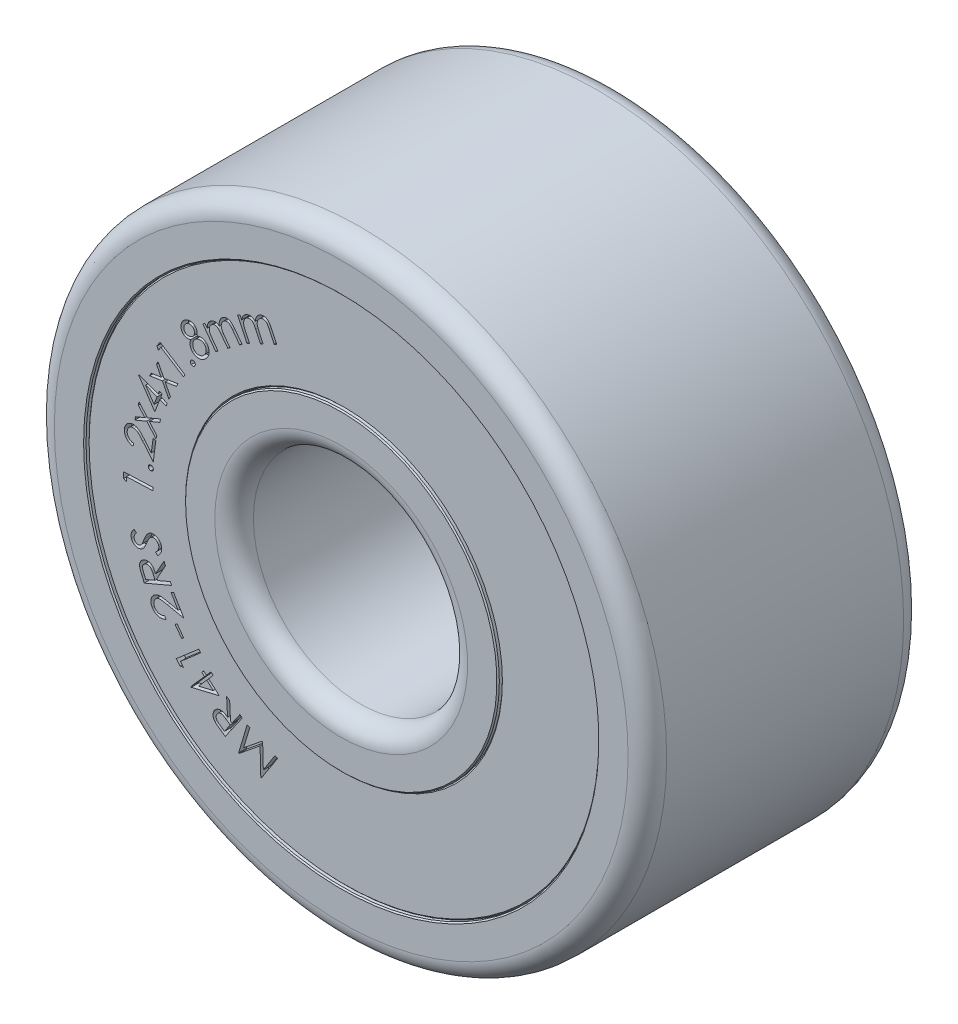
SolidWorks part; units mm, degrees
material "AISI 316 Annealed Stainless Steel Bar (SS)"
ref_plane "Front" through (0, 0, 0) normal (0, 0, 1) x (1, 0, 0)
ref_plane "Top" through (0, 0, 0) normal (0, 1, 0) x (1, 0, 0)
ref_plane "Right" through (0, 0, 0) normal (1, 0, 0) x (0, 0, -1)
sketch "LAYOUT R" plane through (0, 0, 0) normal (1, 0, 0) x (0, 0, -1)
  line L0 (-0.9, 0.7) -> (0.9, 0.7)
  line L1 (0.9, -2) -> (-0.9, -2) construction
  line L2 (0.9, -2) -> (0.9, 2) construction
  line L3 (0.9, 2) -> (-0.9, 2)
  line L4 (-0.9, -2) -> (-0.9, 2) construction
  line L5 (0.9, -2) -> (-0.9, 2) construction
  line L6 (0.9, 2) -> (-0.9, -2) construction
  line L7 (-0.9, 1.025) -> (0.9, 1.025)
  line L8 (-0.9, 1.675) -> (0.9, 1.675)
  line L11 (-17.5, 0) -> (17.5, 0) construction
  line L12 (-0.9, 2) -> (-0.9, 1.675)
  line L13 (0.9, 2) -> (0.9, 1.675)
  line L14 (-0.9, 1.675) -> (-0.9, 1.025)
  line L15 (0.9, 1.675) -> (0.9, 1.025)
  line L16 (-0.9, 1.025) -> (-0.9, 0.7)
  line L17 (0.9, 1.025) -> (0.9, 0.7)
  line L18 (-0.88, 1.675) -> (-0.88, 1.025)
  line L19 (0.88, 1.675) -> (0.88, 1.025)
  point P0 (0, 0)
  point P15 (0, 0)
  dimension "D1" = 1.8
  dimension "D2" = 4
  dimension "D3" = 0.7
  dimension "D6" = 0.02
  dimension "D7" = 0.02
  dimension "D4" = 1.025
  dimension "D5" = 1.675
sketch "Sketch R, INNER BODY" plane through (0, 0, 0) normal (1, 0, 0) x (0, 0, -1)
  line L0 (-0.9, 0.7) -> (0.9, 0.7) construction
  line L2 (-0.9, 1.025) -> (0.9, 1.025) construction
  line L4 (-0.9, 0.7) -> (0.9, 0.7)
  line L6 (-0.9, 1.025) -> (0.9, 1.025)
  line L8 (0.9, 1.025) -> (0.9, 0.7) construction
  line L9 (-0.9, 1.025) -> (-0.9, 0.7) construction
  line L10 (0.9, 1.025) -> (0.9, 0.7)
  line L11 (-0.9, 1.025) -> (-0.9, 0.7)
  line L12 (-17.5, 0) -> (17.5, 0) construction
  line L13 (-17.5, 0) -> (17.5, 0) construction
sketch "Sketch R, OUTER BODY" plane through (0, 0, 0) normal (1, 0, 0) x (0, 0, -1)
  line L2 (-0.9, 1.675) -> (0.9, 1.675) construction
  line L3 (0.9, 2) -> (-0.9, 2) construction
  line L6 (-0.9, 1.675) -> (0.9, 1.675)
  line L7 (0.9, 2) -> (-0.9, 2)
  line L8 (-17.5, 0) -> (17.5, 0) construction
  line L9 (-17.5, 0) -> (17.5, 0) construction
  line L10 (0.9, 2) -> (0.9, 1.675) construction
  line L11 (-0.9, 2) -> (-0.9, 1.675) construction
  line L12 (0.9, 2) -> (0.9, 1.675)
  line L13 (-0.9, 2) -> (-0.9, 1.675)
sketch "Sketch R, SEAL FACES" plane through (0, 0, 0) normal (1, 0, 0) x (0, 0, -1)
  line L0 (-17.5, 0) -> (17.5, 0) construction
  line L1 (-17.5, 0) -> (17.5, 0) construction
  line L3 (-0.9, 1.025) -> (0.9, 1.025) construction
  line L5 (-0.9, 1.675) -> (0.9, 1.675) construction
  line L7 (-0.88, 1.025) -> (0.88, 1.025)
  line L9 (-0.88, 1.675) -> (0.88, 1.675)
  line L10 (0.88, 1.675) -> (0.88, 1.025) construction
  line L11 (-0.88, 1.675) -> (-0.88, 1.025) construction
  line L12 (0.88, 1.675) -> (0.88, 1.025)
  line L13 (-0.88, 1.675) -> (-0.88, 1.025)
revolve "Revolve INNER BODY" add sketch "Sketch R, INNER BODY" angle 360 about L13
fillet "Fillet INNER BODY" radius 0.126 2 edges at (0.7, 0, 0.9) (0.7, 0, -0.9)
chamfer "Chamfer INNER BODY" distance 0.008 angle 45 2 edges at (1.025, 0, -0.9) (1.025, 0, 0.9)
revolve "Revolve OUTER BODY" add sketch "Sketch R, OUTER BODY" angle 360 about L9
fillet "Fillet OUTER BODY" radius 0.126 2 edges at (2, 0, -0.9) (2, 0, 0.9)
chamfer "Chamfer OUTER BODY" distance 0.008 angle 45 2 edges at (1.675, 0, 0.9) (1.675, 0, -0.9)
revolve "Revolve SEALS" add sketch "Sketch R, SEAL FACES" angle 360 about L1
chamfer "Chamfer SEALS" distance 0.008 angle 45 4 edges at (1.025, 0, -0.88) (1.675, 0, -0.88) (1.675, 0, 0.88) (1.025, 0, 0.88)
sketch "Sketch TEXT RADIUS 1 — MANUALLY ASSIGN TEXT AND FONT SIZE (FROM EQUATIONS)" plane through (0, 0, 0.88) normal (0, 0, 1) x (1, 0, 0)
  circle A0 centre (0, 0) radius 1.2525 construction
  text T0 "MR41-2RS  1.2x4x1.8mm" font "Century Gothic" height 0.195
  dimension "D1" = 2.505
extrude "Cut-Extrude SEAL LABEL 1" cut sketch "Sketch TEXT RADIUS 1 — MANUALLY ASSIGN TEXT AND FONT SIZE (FROM EQUATIONS)" against normal blind 0.05
sketch "Sketch TEXT RADIUS 2 — MANUALLY ASSIGN TEXT AND FONT SIZE (FROM EQUATIONS)" plane through (0, 0, -0.88) normal (0, 0, -1) x (-1, 0, 0)
  circle A0 centre (0, 0) radius 1.2525 construction
  text T0 "MR41-2RS  1.2x4x1.8mm" font "Century Gothic" height 0.195
  dimension "D1" = 2.505
extrude "Cut-Extrude SEAL LABEL 2" cut sketch "Sketch TEXT RADIUS 2 — MANUALLY ASSIGN TEXT AND FONT SIZE (FROM EQUATIONS)" against normal blind 0.05
equation "\"_i__BORE\"= 1.4"
equation "\"_i__OUTSIDE_DIAMETER\"= 4"
equation "\"_i__WIDTH\"= 1.8"
equation "\"_i_optional__TEXT_RADIUS_ADJUSTMENT\"= 0"
equation "\"_output__FONT_SIZE_mm\"= \"BODY_SPAN__SEAL__OF_RADIUS\" * \"param__FONT_SIZE_RATIO\"'MANUALLY ASSIGN TO FONT"
equation "\"BODY__HALF_WIDTH\"= \"_i__WIDTH\" / 2"
equation "\"BODY_SPAN___OF_DIAMETER\"= \"_i__OUTSIDE_DIAMETER\" - \"_i__BORE\""
equation "\"BODY_SPAN___OF_RADIUS\"= \"BODY_SPAN___OF_DIAMETER\" / 2"
equation "\"BODY_SPAN__BORE_AND_OD__OF RADIUS\"= ( \"BODY_SPAN___OF_RADIUS\" - \"BODY_SPAN__SEAL__OF_RADIUS\" ) / 2"
equation "\"BODY_SPAN__SEAL__OF_RADIUS\"= \"BODY_SPAN___OF_RADIUS\" * \"param__SEAL_PANEL_SPAN__RATIO_OF_BODY_RADIAN\""
equation "\"BORE__RADIUS\"= \"_i__BORE\" / 2"
equation "\"CORNER_RADII\"= \"_i__WIDTH\" * \"param__CORNER_RADII__ISO_MAX_RATIO_TO_WIDTH\""
equation "\"param__CORNER_RADII__ISO_MAX_RATIO_TO_WIDTH\"= 0.07'WHERE WIDTH IS LESS THAN DIAMETER"
equation "\"param__FONT_SIZE_RATIO\"= 0.3"
equation "\"param__SEAL_FACE_INSET__RATIO_OF_WIDTH\"= .01"
equation "\"param__SEAL_PANEL_SPAN__RATIO_OF_BODY_RADIAN\"= 0.5"
equation "\"param__SIDE_CHAMFERS__RATIO_TO_OD\"= 1 / 500"
equation "\"RING_INNER__OUTSIDE_RADIUS\"= \"BORE__RADIUS\" + \"BODY_SPAN__BORE_AND_OD__OF RADIUS\""
equation "\"RING_OUTER__OUTSIDE_RADIUS\"= ( \"_i__OUTSIDE_DIAMETER\" / 2 ) - \"BODY_SPAN__BORE_AND_OD__OF RADIUS\""
equation "\"SEAL_FACE_INSET\"= \"_i__WIDTH\" * \"param__SEAL_FACE_INSET__RATIO_OF_WIDTH\""
equation "\"SIDE_FACE_AND_SEAL_CHAMFERS\"= \"_i__OUTSIDE_DIAMETER\" * \"param__SIDE_CHAMFERS__RATIO_TO_OD\""
equation "\"TEXT_RADIUS\"= \"_i__BORE\" + ( \"BODY_SPAN___OF_DIAMETER\" / 2 ) - \"_output__FONT_SIZE_mm\" + \"_i_optional__TEXT_RADIUS_ADJUSTMENT\""
equation "\"D1@Chamfer INNER BODY\"=\"SIDE_FACE_AND_SEAL_CHAMFERS\""
equation "\"D1@Chamfer OUTER BODY\"=\"SIDE_FACE_AND_SEAL_CHAMFERS\""
equation "\"D1@Chamfer SEALS\"=\"SIDE_FACE_AND_SEAL_CHAMFERS\""
equation "\"D1@Fillet INNER BODY\"=\"CORNER_RADII\""
equation "\"D1@Fillet OUTER BODY\"=\"CORNER_RADII\""
equation "\"D1@LAYOUT R\"=\"_i__WIDTH\""
equation "\"D1@Sketch TEXT RADIUS 1 — MANUALLY ASSIGN TEXT AND FONT SIZE (FROM EQUATIONS)\" = \"TEXT_RADIUS\""
equation "\"D1@Sketch TEXT RADIUS 2 — MANUALLY ASSIGN TEXT AND FONT SIZE (FROM EQUATIONS)\" = \"TEXT_RADIUS\""
equation "\"D2@LAYOUT R\"=\"_i__OUTSIDE_DIAMETER\""
equation "\"D3@LAYOUT R\"=\"BORE__RADIUS\""
equation "\"D4@LAYOUT R\"=\"RING_INNER__OUTSIDE_RADIUS\""
equation "\"D5@LAYOUT R\"=\"RING_OUTER__OUTSIDE_RADIUS\""
